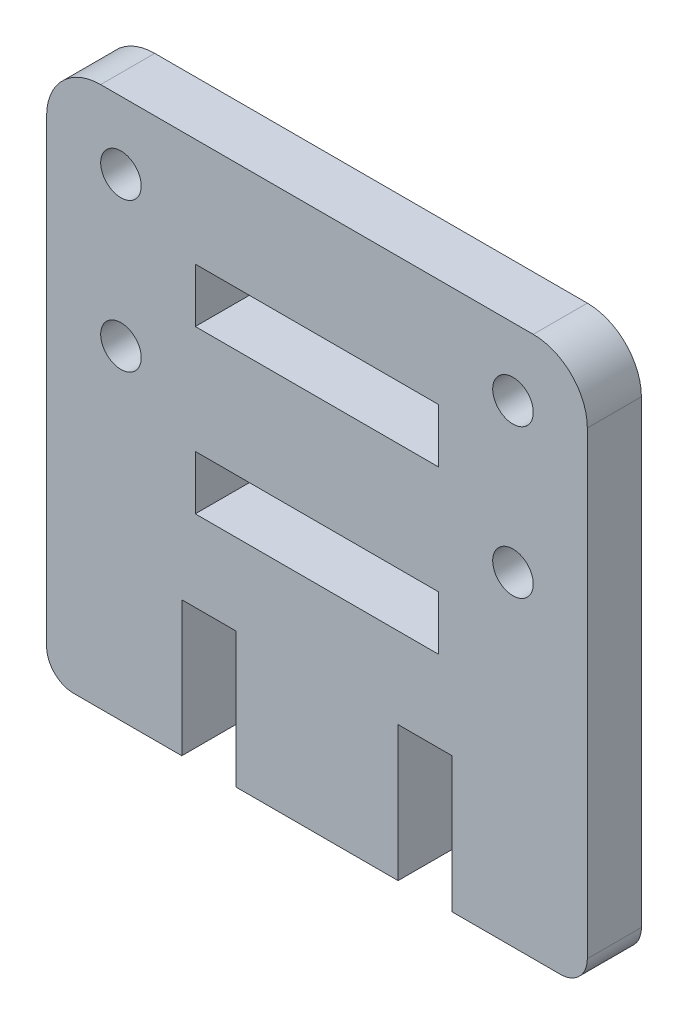
SolidWorks part; units mm, degrees
material "Acrylic (Medium-high impact)"
ref_plane "Front Plane" through (0, 0, 0) normal (0, 0, 1) x (1, 0, 0)
ref_plane "Top Plane" through (0, 0, 0) normal (0, 1, 0) x (1, 0, 0)
ref_plane "Right Plane" through (0, 0, 0) normal (1, 0, 0) x (0, 0, -1)
sketch "Model" plane through (0, 0, 0) normal (0, 0, 1) x (1, 0, 0)
  line L70 (1972.1098, 1171.2847) -> (1972.1098, 1166.2847)
  line L71 (1978.1098, 1171.2847) -> (1978.1098, 1166.2847)
  line L114 (1967.1098, 1186.2847) -> (1983.1098, 1186.2847)
  line L115 (1965.1098, 1184.2847) -> (1965.1098, 1167.2847)
  line L116 (1985.1098, 1184.2847) -> (1985.1098, 1167.2847)
  line L222 (1978.1098, 1171.2847) -> (1980.1098, 1171.2847)
  line L223 (1980.1098, 1171.2847) -> (1980.1098, 1166.2847)
  line L224 (1972.1098, 1171.2847) -> (1970.1098, 1171.2847)
  line L225 (1970.1098, 1171.2847) -> (1970.1098, 1166.2847)
  line L226 (1966.1098, 1166.2847) -> (1970.1098, 1166.2847)
  line L227 (1972.1098, 1166.2847) -> (1978.1098, 1166.2847)
  line L228 (1980.1098, 1166.2847) -> (1984.1098, 1166.2847)
  line L274 (1970.6098, 1182.2847) -> (1979.6098, 1182.2847)
  line L284 (1970.6098, 1174.2847) -> (1979.6098, 1174.2847)
  line L340 (1970.6098, 1180.2847) -> (1979.6098, 1180.2847)
  line L341 (1970.6098, 1176.2847) -> (1979.6098, 1176.2847)
  line L346 (1979.6098, 1174.2847) -> (1979.6098, 1176.2847)
  line L347 (1970.6098, 1174.2847) -> (1970.6098, 1176.2847)
  line L348 (1970.6098, 1180.2847) -> (1970.6098, 1182.2847)
  line L349 (1979.6098, 1180.2847) -> (1979.6098, 1182.2847)
  arc A25 (1984.1098, 1166.2847) -> (1985.1098, 1167.2847) centre (1984.1098, 1167.2847) ccw
  arc A26 (1965.1098, 1167.2847) -> (1966.1098, 1166.2847) centre (1966.1098, 1167.2847) ccw
  arc A43 (1985.1098, 1184.2847) -> (1983.1098, 1186.2847) centre (1983.1098, 1184.2847) ccw
  arc A44 (1967.1098, 1186.2847) -> (1965.1098, 1184.2847) centre (1967.1098, 1184.2847) ccw
  circle A98 centre (1982.3598, 1183.7847) radius 0.75
  circle A99 centre (1967.8598, 1183.7847) radius 0.75
  circle A122 centre (1982.3598, 1178.2847) radius 0.75
  circle A123 centre (1967.8598, 1178.2847) radius 0.75
extrude "Boss-Extrude1" add sketch "Model" along normal blind 2
